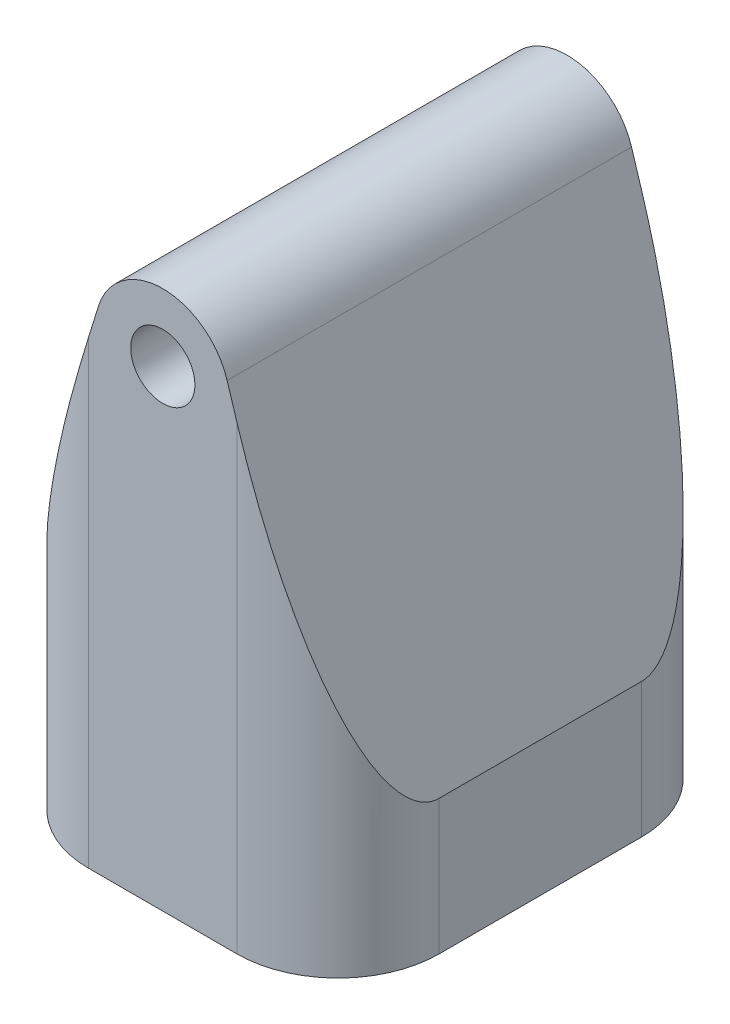
SolidWorks part; units mm, degrees
material "ABS"
ref_plane "Front Plane" through (0, 0, 0) normal (0, 0, 1) x (1, 0, 0)
ref_plane "Top Plane" through (0, 0, 0) normal (0, 1, 0) x (1, 0, 0)
ref_plane "Right Plane" through (0, 0, 0) normal (1, 0, 0) x (0, 0, -1)
sketch "Sketch1" plane through (0, 0, 0) normal (1, 0, 0) x (0, 0, -1)
  line L1 (-15, -20) -> (15, -20)
  line L2 (-15, -20) -> (-15, 20)
  line L3 (-15, 20) -> (15, 20)
  line L4 (15, -20) -> (15, 20)
  line L5 (-15, -20) -> (15, 20) construction
  line L6 (-15, 20) -> (15, -20) construction
  point P0 (0, 0)
  dimension "D1" = 30
  dimension "D2" = 40
extrude "Boss-Extrude1" add sketch "Sketch1" along normal mid plane 26
sketch "Sketch2" plane through (0, 0, 15) normal (0, 0, 1) x (1, 0, 0)
  line L0 (13, -20) -> (-13, -20) construction
  line L1 (-13, -10) -> (-4.775, 16.483)
  line L2 (13, -10) -> (4.775, 16.483)
  line L4 (13, 20) -> (-13, 20) construction
  line L5 (-13, 20) -> (-13, -20) construction
  line L6 (-13, -20) -> (-13, -10)
  line L7 (13, -20) -> (13, -10)
  circle A0 centre (0, 15) radius 2.3813
  arc A1 (-4.775, 16.483) -> (4.775, 16.483) centre (0, 15) cw
  line M1 (-13, 20) -> (-13, -20)
  line M3 (13, -20) -> (13, 20)
  line M4 (13, 20) -> (-13, 20)
  dimension "D1" = 4.7625
  dimension "D3" = 10
  dimension "D2" = 35
extrude "Cut-Extrude1" cut sketch "Sketch2" against normal through all contours L1 A1 M4 M1 | A0 | A1 L2 M4 M3
sketch "Sketch3" plane through (0, -20, 0) normal (0, -1, 0) x (1, 0, 0)
  line L0 (13, -15) -> (-13, -15) construction
  circle A0 centre (0, 10) radius 2.8067
  circle A1 centre (0, -10) radius 2.8067
  circle A2 centre (-10, 0) radius 2.8067
  circle A3 centre (10, 0) radius 2.8067
  point P4 (0, 0)
  point P7 (0, -15)
  point P11 (-9.2783, 0)
  point P12 (-10, 0)
  point P13 (-10, 0)
  point P16 (4.3675, 1.0361)
  point P17 (0, 0)
  point P19 (-0.52, -0.997)
  dimension "D1" = 5.6134
  dimension "D2" = 20
  dimension "D3" = 10
  dimension "D4" = 10
  dimension "D5" = 10
extrude "Cut-Extrude2" cut sketch "Sketch3" against normal blind 10
fillet "Fillet1" radius 7.5 4 edges at (-13, -15, -15) (-13, -15, 15) (13, -15, 15) (13, -15, -15)
